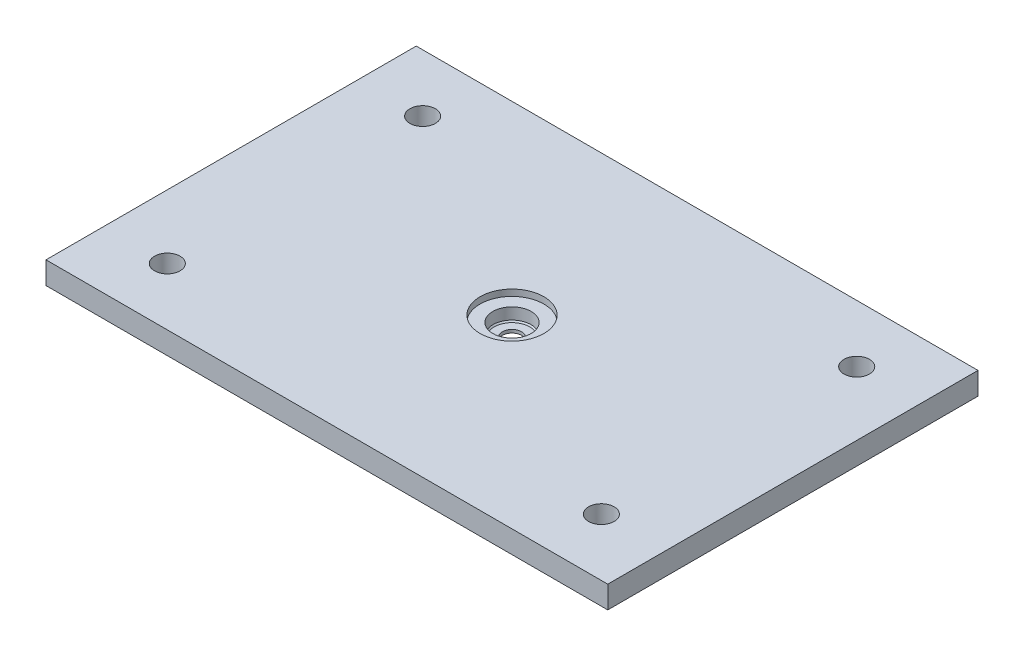
SolidWorks part; units mm, degrees
ref_plane "Front Plane" through (0, 0, 0) normal (0, 0, 1) x (1, 0, 0)
ref_plane "Top Plane" through (0, 0, 0) normal (0, 1, 0) x (1, 0, 0)
ref_plane "Right Plane" through (0, 0, 0) normal (1, 0, 0) x (0, 0, -1)
sketch "Sketch1" plane through (0, 0, 0) normal (0, 1, 0) x (1, 0, 0)
  line L1 (-440, 290) -> (440, 290)
  line L2 (-440, 290) -> (-440, -290)
  line L3 (-440, -290) -> (440, -290)
  line L4 (440, 290) -> (440, -290)
  line L6 (-440, 0) -> (440, 0) construction
  point P0 (0, 0)
extrude "Boss-Extrude1" add sketch "Sketch1" along normal blind 35
sketch "Sketch2" plane through (0, 35, 0) normal (0, 1, 0) x (1, 0, 0)
  circle A0 centre (0, 0) radius 50
extrude "Cut-Extrude1" cut sketch "Sketch2" against normal blind 10
sketch "Sketch3" plane through (0, 25, 0) normal (0, 1, 0) x (1, 0, 0)
  circle A0 centre (0, 0) radius 30
extrude "Cut-Extrude2" cut sketch "Sketch3" against normal blind 20
sketch "Sketch4" plane through (0, 5, 0) normal (0, 1, 0) x (1, 0, 0)
  circle A0 centre (0, 0) radius 15
extrude "Cut-Extrude3" cut sketch "Sketch4" against normal blind 522
chamfer "Chamfer1" distance 2 angle 45 1 edges at (0, 5, 30)
sketch "Sketch5" plane through (0, 35, 0) normal (0, 1, 0) x (1, 0, 0)
  circle A0 centre (-340, 200) radius 20
  circle A1 centre (340, 200) radius 20
  circle A2 centre (340, -200) radius 20
  circle A3 centre (-340, -200) radius 20
  dimension "D1" = 680
extrude "Cut-Extrude4" cut sketch "Sketch5" against normal blind 450
